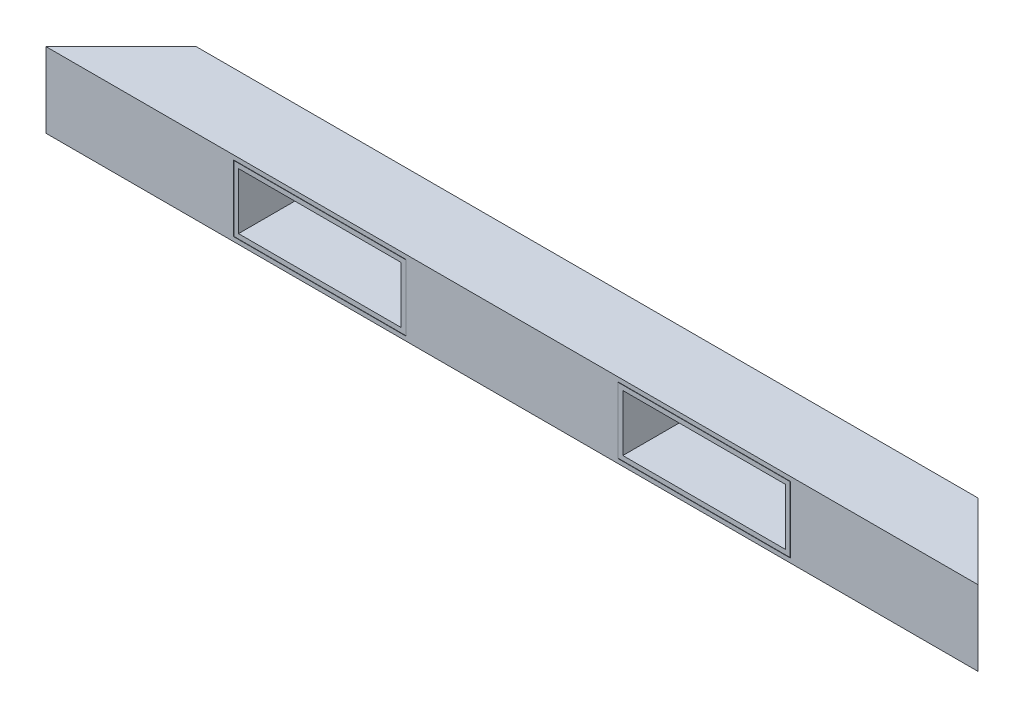
SolidWorks part; units mm, degrees
ref_plane "Alzado" through (0, 0, 0) normal (0, 0, 1) x (1, 0, 0)
ref_plane "Planta" through (0, 0, 0) normal (0, 1, 0) x (1, 0, 0)
ref_plane "Vista lateral" through (0, 0, 0) normal (1, 0, 0) x (0, 0, -1)
sketch "Croquis1" plane through (0, 0, 0) normal (0, 0, 1) x (1, 0, 0)
  line L1 (0, 0) -> (1260.95, 0)
  line L2 (0, 0) -> (0, 101.6)
  line L3 (0, 101.6) -> (1260.95, 101.6)
  line L4 (1260.95, 0) -> (1260.95, 101.6)
  dimension "D1" = 1260.95
  dimension "D2" = 101.6
extrude "Saliente-Extruir1" add sketch "Croquis1" along normal blind 101.6
sketch "Croquis5" plane through (1260.95, 0, 0) normal (1, 0, 0) x (0, 0, -1)
  line L0 (-101.6, 50.8) -> (-50.8, 50.8) construction
  line L1 (-101.6, 0) -> (-101.6, 101.6) construction
  line L2 (-50.8, 50.8) -> (-50.8, 101.6) construction
  line L3 (-101.6, 101.6) -> (0, 101.6) construction
  line L4 (0, 0) -> (0, 101.6) construction
  line L5 (-6.35, 6.35) -> (-95.25, 6.35)
  line L6 (-6.35, 6.35) -> (-6.35, 95.25)
  line L7 (-6.35, 95.25) -> (-95.25, 95.25)
  line L8 (-95.25, 6.35) -> (-95.25, 95.25)
  line L9 (-6.35, 6.35) -> (-95.25, 95.25) construction
  line L10 (-6.35, 95.25) -> (-95.25, 6.35) construction
  dimension "D1" = 6.35
  dimension "D2" = 6.35
extrude "Cortar-Extruir4" cut sketch "Croquis5" against normal up to surface (1260.95 mm away) up to face at (0, 50.8, 50.8)
sketch "Croquis6" plane through (0, 101.6, 0) normal (0, 1, 0) x (1, 0, 0)
  line L0 (0, 0) -> (101.6, 0)
  line L1 (1260.95, 0) -> (0, 0) construction
  line L2 (101.6, 0) -> (0, -101.6)
  line L3 (0, -101.6) -> (0, 0)
  line L4 (630.475, -101.6) -> (630.475, 0) construction
  line L5 (1260.95, -101.6) -> (0, -101.6) construction
  line L6 (1260.95, -101.6) -> (1260.95, 0)
  line L7 (1159.35, 0) -> (1260.95, -101.6)
  line L8 (1260.95, 0) -> (1159.35, 0)
  dimension "D1" = 101.6
extrude "Cortar-Extruir5" cut sketch "Croquis6" against normal blind 101.6
sketch "Croquis7" plane through (0, 0, 101.6) normal (0, 0, 1) x (1, 0, 0)
  line L0 (0, 50.8) -> (1260.95, 50.8) construction
  line L1 (0, 101.6) -> (0, 0) construction
  line L2 (1260.95, 0) -> (1260.95, 101.6) construction
  line L3 (630.475, 0) -> (630.475, 101.6) construction
  line L4 (480.475, 12.7) -> (260.475, 12.7)
  line L5 (480.475, 12.7) -> (480.475, 88.9)
  line L6 (480.475, 88.9) -> (260.475, 88.9)
  line L7 (260.475, 12.7) -> (260.475, 88.9)
  line L8 (480.475, 12.7) -> (260.475, 88.9) construction
  line L9 (480.475, 88.9) -> (260.475, 12.7) construction
  line L10 (0, 0) -> (1260.95, 0) construction
  line L11 (1260.95, 101.6) -> (0, 101.6) construction
  line L13 (1000.475, 12.7) -> (780.475, 12.7)
  line L14 (1000.475, 12.7) -> (1000.475, 88.9)
  line L15 (1000.475, 88.9) -> (780.475, 88.9)
  line L16 (780.475, 12.7) -> (780.475, 88.9)
  line L17 (1000.475, 12.7) -> (780.475, 88.9) construction
  line L18 (1000.475, 88.9) -> (780.475, 12.7) construction
  point P6 (370.475, 50.8)
  point P17 (890.475, 50.8)
  dimension "D1" = 76.2
  dimension "D2" = 220
  dimension "D3" = 150
  dimension "D4" = 220
  dimension "D5" = 76.2
  dimension "D6" = 150
extrude "Cortar-Extruir6" cut sketch "Croquis7" against normal up to surface (101.6 mm away) up to face at (630.475, 50.8, 0)
sketch "Croquis8" plane through (0, 0, 101.6) normal (0, 0, 1) x (1, 0, 0)
  line L0 (630.475, 0) -> (630.475, 101.6) construction
  line L1 (260.475, 88.9) -> (480.475, 88.9)
  line L2 (260.475, 88.9) -> (260.475, 12.7)
  line L3 (260.475, 12.7) -> (480.475, 12.7)
  line L4 (480.475, 88.9) -> (480.475, 12.7)
  line L5 (486.825, 6.35) -> (254.125, 6.35)
  line L6 (486.825, 6.35) -> (486.825, 95.25)
  line L7 (486.825, 95.25) -> (254.125, 95.25)
  line L8 (254.125, 6.35) -> (254.125, 95.25)
  line L9 (486.825, 6.35) -> (254.125, 95.25) construction
  line L10 (486.825, 95.25) -> (254.125, 6.35) construction
  line L11 (0, 0) -> (1260.95, 0) construction
  line L12 (1260.95, 101.6) -> (0, 101.6) construction
  line L13 (774.125, 95.25) -> (1006.825, 6.35) construction
  line L14 (774.125, 6.35) -> (1006.825, 95.25) construction
  line L15 (1006.825, 6.35) -> (1006.825, 95.25)
  line L16 (774.125, 95.25) -> (1006.825, 95.25)
  line L17 (774.125, 6.35) -> (774.125, 95.25)
  line L18 (774.125, 6.35) -> (1006.825, 6.35)
  line L19 (780.475, 88.9) -> (780.475, 12.7)
  line L20 (1000.475, 12.7) -> (780.475, 12.7)
  line L21 (1000.475, 88.9) -> (1000.475, 12.7)
  line L22 (1000.475, 88.9) -> (780.475, 88.9)
  point P6 (370.475, 50.8)
  point P25 (890.475, 50.8)
  dimension "D1" = 6.35
  dimension "D2" = 6.35
  dimension "D3" = 6.35
  dimension "D4" = 6.35
extrude "Saliente-Extruir2" add sketch "Croquis8" against normal up to surface (101.6 mm away) up to face at (890.475, 50.8, 0)
sketch "Croquis9" plane through (0, 0, 101.6) normal (0, 0, 1) x (1, 0, 0)
  line L0 (370.475, 88.9) -> (370.475, 12.7) construction
  line L1 (480.475, 88.9) -> (260.475, 88.9) construction
  line L2 (260.475, 12.7) -> (480.475, 12.7) construction
  line L3 (480.475, 12.7) -> (480.475, 88.9) construction
  line L4 (486.825, 6.35) -> (254.125, 6.35)
  line L5 (486.825, 6.35) -> (486.825, 95.25)
  line L6 (486.825, 95.25) -> (254.125, 95.25)
  line L7 (254.125, 6.35) -> (254.125, 95.25)
  line L8 (486.825, 6.35) -> (254.125, 95.25) construction
  line L9 (486.825, 95.25) -> (254.125, 6.35) construction
  line L10 (630.475, 0) -> (630.475, 101.6) construction
  line L11 (487.325, 5.85) -> (253.625, 5.85)
  line L12 (487.325, 5.85) -> (487.325, 95.75)
  line L13 (487.325, 95.75) -> (253.625, 95.75)
  line L14 (253.625, 5.85) -> (253.625, 95.75)
  line L15 (487.325, 5.85) -> (253.625, 95.75) construction
  line L16 (487.325, 95.75) -> (253.625, 5.85) construction
  line L17 (0, 0) -> (1260.95, 0) construction
  line L18 (1260.95, 101.6) -> (0, 101.6) construction
  line L19 (773.625, 95.75) -> (1007.325, 5.85) construction
  line L20 (773.625, 5.85) -> (1007.325, 95.75) construction
  line L21 (774.125, 95.25) -> (1006.825, 6.35) construction
  line L22 (774.125, 6.35) -> (1006.825, 95.25) construction
  line L23 (890.475, 88.9) -> (890.475, 12.7) construction
  line L24 (1007.325, 5.85) -> (1007.325, 95.75)
  line L25 (773.625, 95.75) -> (1007.325, 95.75)
  line L26 (773.625, 5.85) -> (773.625, 95.75)
  line L27 (773.625, 5.85) -> (1007.325, 5.85)
  line L28 (1006.825, 6.35) -> (1006.825, 95.25)
  line L29 (774.125, 95.25) -> (1006.825, 95.25)
  line L30 (774.125, 6.35) -> (774.125, 95.25)
  line L31 (774.125, 6.35) -> (1006.825, 6.35)
  point P6 (370.475, 50.8)
  point P13 (370.475, 50.8)
  point P34 (890.475, 50.8)
  dimension "D1" = 6.35
  dimension "D2" = 6.35
  dimension "D3" = 0.5
  dimension "D4" = 0.5
extrude "Cortar-Extruir7" cut sketch "Croquis9" against normal up to surface (101.6 mm away) up to face at (630.475, 50.8, 0)
